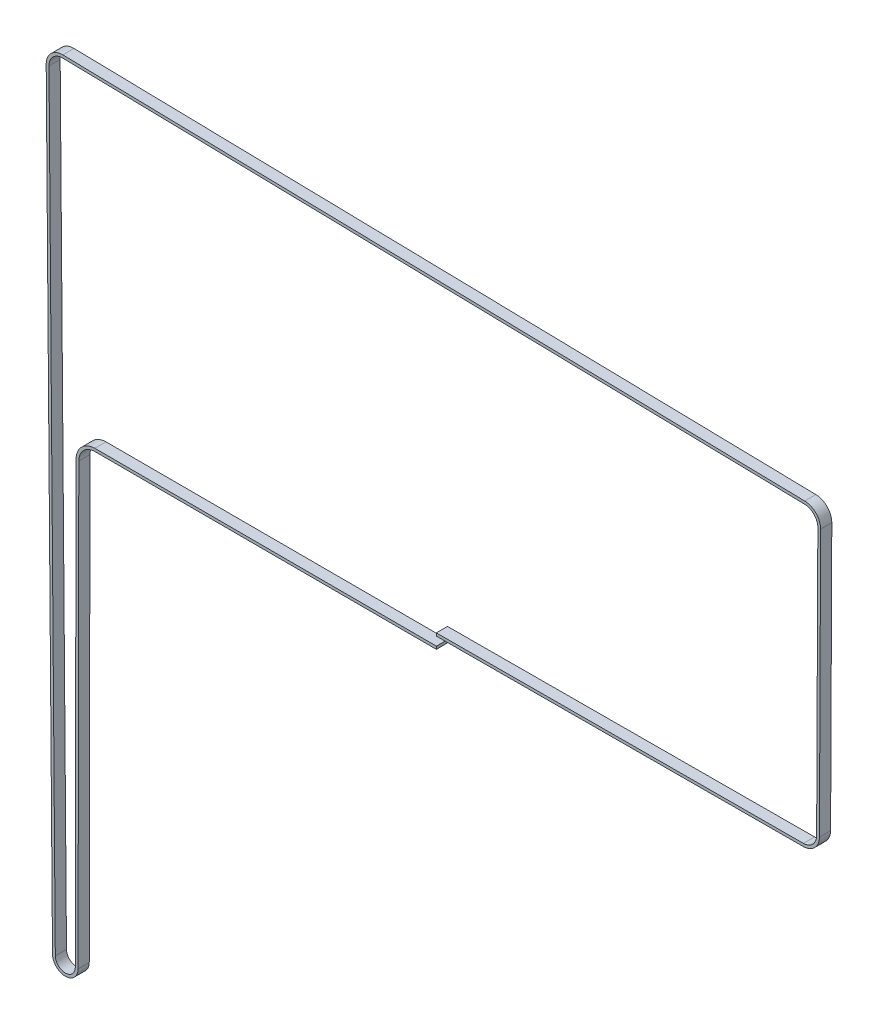
SolidWorks part; units mm, degrees
material "Резина"
ref_plane "Спереди" through (0, 0, 0) normal (0, 0, 1) x (1, 0, 0)
ref_plane "Сверху" through (0, 0, 0) normal (0, 1, 0) x (1, 0, 0)
ref_plane "Справа" through (0, 0, 0) normal (1, 0, 0) x (0, 0, -1)
sketch "Эскиз1" plane through (0, 0, 0) normal (0, 0, 1) x (1, 0, 0)
  line B0 (-6.8585, -0.0565) -> (-10.2497, 411.928)
  line B1 (-1.3179, 420.7481) -> (396.8293, 412.4586)
  line B2 (405.3971, 403.671) -> (404.7499, 260.1848)
  line B3 (7.25, 236.2388) -> (6.8587, -0.0114)
  arc B4 (6.8587, -0.0114) -> (-6.8585, -0.0565) centre (0, 0) cw
  arc B5 (-10.2497, 411.928) -> (-1.3179, 420.7481) centre (-1.5, 412) cw
  arc B6 (396.8293, 412.4586) -> (405.3971, 403.671) centre (396.6472, 403.7105) cw
  arc B7 (404.7499, 260.1848) -> (396.1496, 251.4756) centre (396, 260.2243) cw
  arc B8 (15.8504, 244.973) -> (7.25, 236.2388) centre (16, 236.2243) ccw
  line B9 (15.8504, 244.973) -> (199.171, 244.6694)
  line B10 (396.1496, 251.4756) -> (199.1204, 250.818)
sketch_block_instance "Блок-ремень1-1"
sketch_block "Блок-ремень1"
extrude "Вытянуть-Тонкостенный1" add sketch "Эскиз1" along normal blind 6 thin
